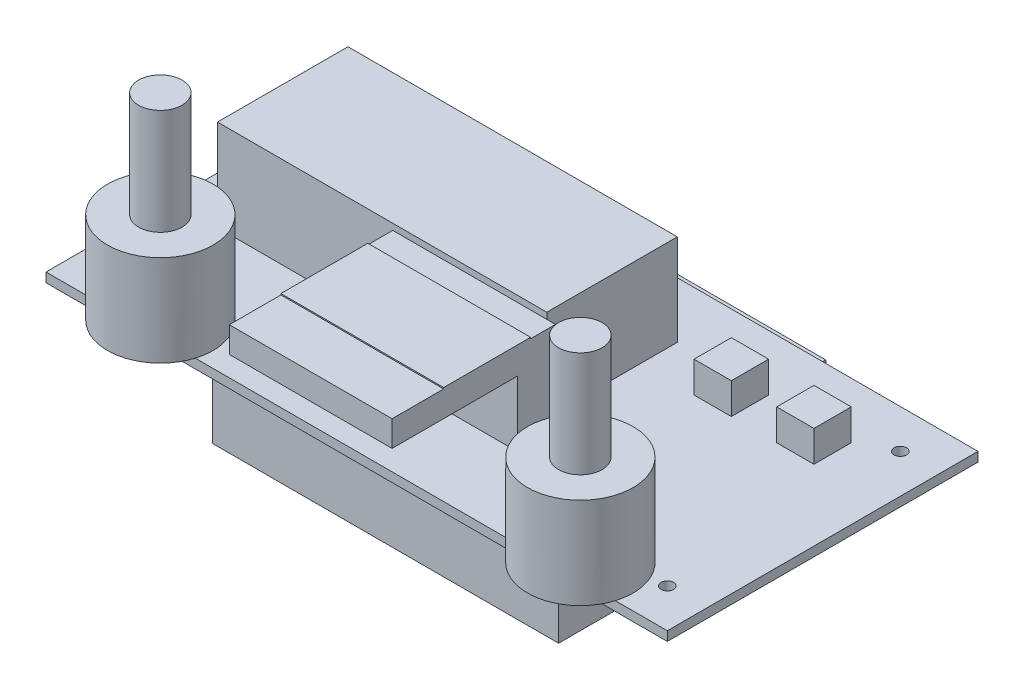
SolidWorks part; units mm, degrees
ref_plane "Plano frontal" through (0, 0, 0) normal (0, 0, 1) x (1, 0, 0)
ref_plane "Plano superior" through (0, 0, 0) normal (0, 1, 0) x (1, 0, 0)
ref_plane "Plano direito" through (0, 0, 0) normal (1, 0, 0) x (0, 0, -1)
sketch "Esboço1" plane through (0, 0, 0) normal (0, 1, 0) x (1, 0, 0)
  line L1 (-50, 25) -> (50, 25)
  line L2 (-50, 25) -> (-50, -25)
  line L3 (-50, -25) -> (50, -25)
  line L4 (50, 25) -> (50, -25)
  line L5 (-50, 25) -> (50, -25) construction
  line L6 (-50, -25) -> (50, 25) construction
  circle A0 centre (43.75, 18.75) radius 1
  circle A1 centre (43.75, -18.75) radius 1
  circle A2 centre (-43.75, 18.75) radius 1
  circle A3 centre (-43.7512, -18.75) radius 1
  point P0 (0, 0)
  point P8 (22.0338, 2.573)
  point P9 (0, 0)
  point P12 (0, 0)
  point P13 (0, 0)
  point P14 (0, 0)
  point P15 (23.3535, 35.1351)
  point P16 (0, 0)
  point P19 (-3.6423, 35.1351)
  point P22 (-3.6423, 28.4541)
  point P23 (-2.9689, 37.1545)
  point P24 (15.2808, 35.1351)
  point P25 (15.2808, -2.3649)
  point P28 (-45.8431, -29.4892)
  dimension "D3" = 37.5
  dimension "D1" = 100
  dimension "D2" = 50
  dimension "D4" = 37.5
  dimension "D5" = 87.5
  dimension "D6" = 6.25
  dimension "D7" = 6.25
  dimension "D8" = 6.25
  dimension "D9" = 87.5012
extrude "Ressalto-extrusão1" add sketch "Esboço1" along normal blind 1.5
sketch "Esboço2" plane through (0, 1.5, 0) normal (0, 1, 0) x (1, 0, 0)
  line L0 (50, 25) -> (-50, 25) construction
  line L1 (-42.4, 16) -> (10.6, 16)
  line L2 (-42.4, 16) -> (-42.4, -5)
  line L3 (-42.4, -5) -> (10.6, -5)
  line L4 (10.6, 16) -> (10.6, -5)
  line L5 (19.3, 16) -> (25.3, 16)
  line L6 (19.3, 16) -> (19.3, 10)
  line L7 (19.3, 10) -> (25.3, 10)
  line L8 (25.3, 16) -> (25.3, 10)
  line L9 (32.6, 16) -> (38.6, 16)
  line L10 (32.6, 16) -> (32.6, 10)
  line L11 (32.6, 10) -> (38.6, 10)
  line L12 (38.6, 16) -> (38.6, 10)
  line L13 (-13.2, -6) -> (13, -6)
  line L14 (-13.2, -6) -> (-13.2, -32.3)
  line L15 (-13.2, -32.3) -> (13, -32.3)
  line L16 (13, -6) -> (13, -32.3)
  line L17 (-50, 25) -> (-50, -25) construction
  line L18 (50, -25) -> (50, 25) construction
  line L19 (-47.4896, -31) -> (61.9648, -31) construction
  line L20 (-50, -25) -> (50, -25) construction
  circle A0 centre (33.5, -22.5) radius 8.5
  circle A1 centre (-34.1, -22.5) radius 8.5
  dimension "D17" = 17
  dimension "D18" = 17
  dimension "D20" = 15.9
  dimension "D1" = 21
  dimension "D2" = 53
  dimension "D3" = 9
  dimension "D4" = 7.6
  dimension "D5" = 6
  dimension "D6" = 6
  dimension "D7" = 6
  dimension "D8" = 6
  dimension "D9" = 7.3
  dimension "D10" = 11.4
  dimension "D11" = 9
  dimension "D12" = 9
  dimension "D13" = 26.2
  dimension "D14" = 26.3
  dimension "D15" = 31
  dimension "D16" = 36.8
  dimension "D19" = 6
  dimension "D21" = 16.5
extrude "Ressalto-extrusão4" add sketch "Esboço2" along normal blind 14.7
sketch "Esboço3" plane through (0, 16.2, 0) normal (0, 1, 0) x (1, 0, 0)
  line L1 (38.6, 10) -> (15.7082, 10)
  line L2 (38.6, 10) -> (38.6, 18.05)
  line L3 (38.6, 18.05) -> (15.7082, 18.05)
  line L4 (15.7082, 10) -> (15.7082, 18.05)
extrude "Corte-extrusão1" cut sketch "Esboço3" against normal blind 9.7
sketch "Esboço4" plane through (0, 16.2, 0) normal (0, 1, 0) x (1, 0, 0)
  circle A0 centre (33.5, -22.5) radius 3.5
  circle A1 centre (-34.1, -22.5) radius 3.5
  dimension "D1" = 7
  dimension "D2" = 7
extrude "Ressalto-extrusão5" add sketch "Esboço4" along normal blind 17
sketch "Esboço5" plane through (0, 0, 0) normal (0, -1, 0) x (1, 0, 0)
  line L0 (-50, -25) -> (-50, 25) construction
  line L1 (-32.2, 16) -> (23.5, 16)
  line L2 (-32.2, 16) -> (-32.2, -27)
  line L3 (-32.2, -27) -> (23.5, -27)
  line L4 (23.5, 16) -> (23.5, -27)
  line L5 (-32.2, 16) -> (23.5, -27) construction
  line L6 (-32.2, -27) -> (23.5, 16) construction
  line L7 (50, 25) -> (50, -25) construction
  line L8 (-50, 25) -> (50, 25) construction
  point P0 (-4.35, -5.5)
  point P5 (21.1431, -5.8952)
  dimension "D1" = 17.8
  dimension "D2" = 26.5
  dimension "D3" = 9
  dimension "D4" = 43
extrude "Ressalto-extrusão6" add sketch "Esboço5" along normal blind 18
sketch "Esboço6" plane through (0, 16.2, 0) normal (0, 1, 0) x (1, 0, 0)
  line L0 (-13.2, -6) -> (-13.2, -25) construction
  line L1 (-13.2, -10) -> (13, -10)
  line L2 (-13.2, -10) -> (-13.2, -24)
  line L3 (-13.2, -24) -> (13, -24)
  line L4 (13, -10) -> (13, -24)
  line L5 (13, -25) -> (13, -6) construction
  line L6 (13, -6) -> (-13.2, -6) construction
  dimension "D1" = 14
  dimension "D2" = 4
extrude "Ressalto-extrusão7" add sketch "Esboço6" along normal blind 0.2
sketch "Esboço7" plane through (0, 0, 32.3) normal (0, 0, 1) x (1, 0, 0)
  line L0 (-13.2, 16.2) -> (-13.2, 1.5) construction
  line L1 (-13.2, 12.06) -> (13, 12.06)
  line L2 (-13.2, 12.06) -> (-13.2, 1.5)
  line L3 (-13.2, 1.5) -> (13, 1.5)
  line L4 (13, 12.06) -> (13, 1.5)
extrude "Corte-extrusão2" cut sketch "Esboço7" against normal blind 20.2
